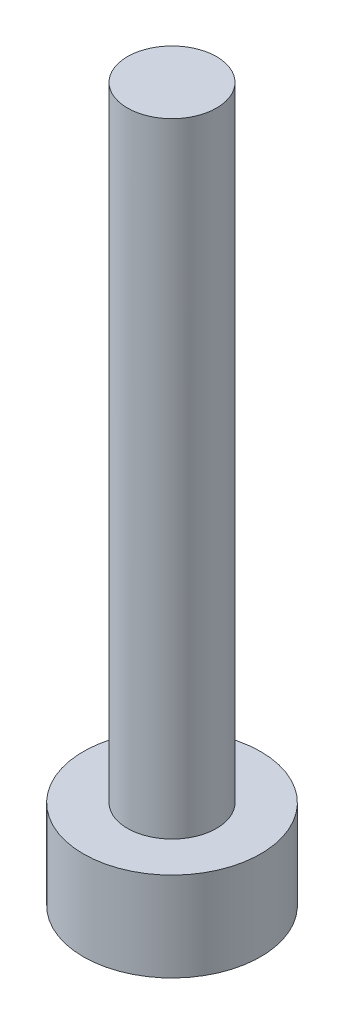
SolidWorks part; units mm, degrees
ref_plane "前视基准面" through (0, 0, 0) normal (0, 0, 1) x (1, 0, 0)
ref_plane "上视基准面" through (0, 0, 0) normal (0, 1, 0) x (1, 0, 0)
ref_plane "右视基准面" through (0, 0, 0) normal (1, 0, 0) x (0, 0, -1)
sketch "草图1" plane through (0, 0, 0) normal (0, 1, 0) x (1, 0, 0)
  circle A0 centre (0, 0) radius 1
  dimension "D1" = 2
extrude "凸台-拉伸1" add sketch "草图1" along normal blind 14
sketch "草图2" plane through (0, 0, 0) normal (0, -1, 0) x (1, 0, 0)
  circle A0 centre (0, 0) radius 1.99
  dimension "D1" = 3.98
extrude "凸台-拉伸2" add sketch "草图2" along normal blind 2
